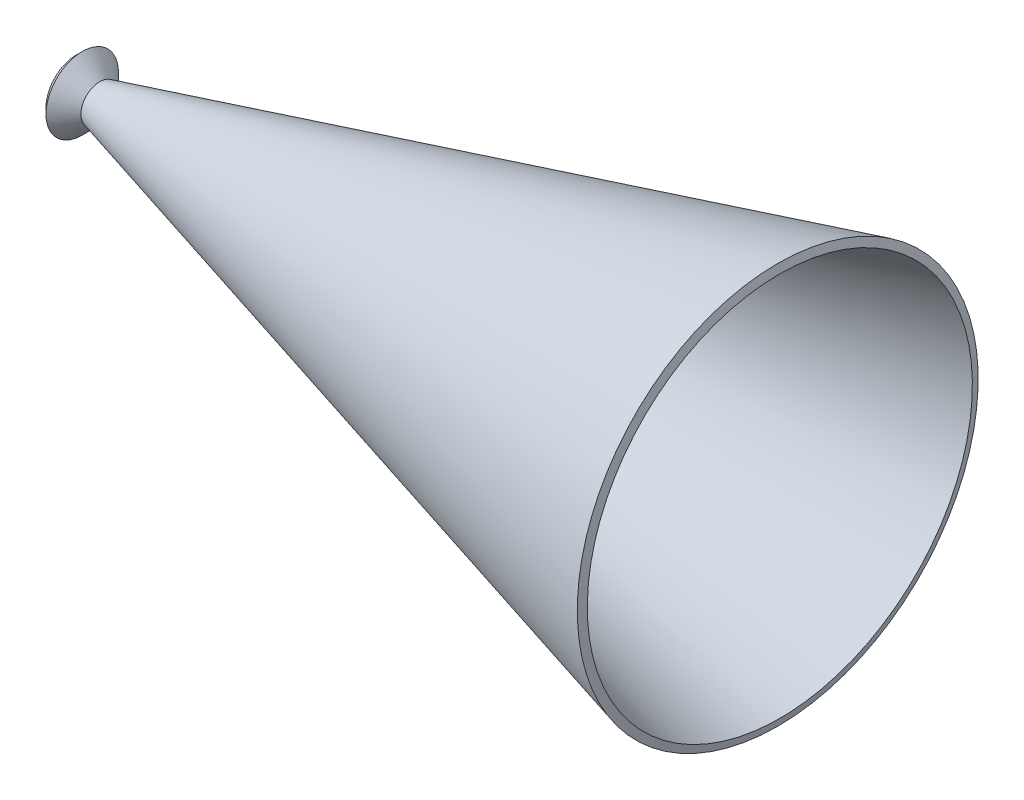
SolidWorks part; units mm, degrees
ref_plane "Piano frontale" through (0, 0, 0) normal (0, 0, 1) x (1, 0, 0)
ref_plane "Piano superiore" through (0, 0, 0) normal (0, 1, 0) x (1, 0, 0)
ref_plane "Piano destro" through (0, 0, 0) normal (1, 0, 0) x (0, 0, -1)
sketch "Schizzo1" plane through (0, 0, 0) normal (0, 0, 1) x (1, 0, 0)
  line L0 (-12.7, 18.5733) -> (0, 5.8733)
  line L1 (0, 5.8733) -> (416.5, 117.4741)
  line L2 (-136.4061, 5.8733) -> (136.4061, 5.8733) construction
  line L4 (1.4943, 11.4501) -> (415.2059, 122.3038)
  line L5 (415.2059, 122.3038) -> (416.5, 117.4741)
  line L6 (-12.7, 18.5733) -> (-9.1645, 22.1088)
  line L7 (-9.1645, 22.1088) -> (1.4943, 11.4501)
  point P12 (-33.1934, 2.1555)
  point P13 (4.9879, 12.2233)
  point P14 (3.3499, 9.5945)
  point P15 (0, 0)
  dimension "D1" = 5.8733
  dimension "D2" = 45
  dimension "D3" = 12.7
  dimension "D4" = 416.5
  dimension "D5" = 15
  dimension "D6" = 90
  dimension "D7" = 5
  dimension "D8" = 90
sketch "Schizzo2" plane through (0, 0, 0) normal (0, 0, 1) x (1, 0, 0)
  line L0 (-119.9672, 0) -> (119.9672, 0)
revolve "Rivoluzione1" add sketch "Schizzo1" angle 360 about L0
